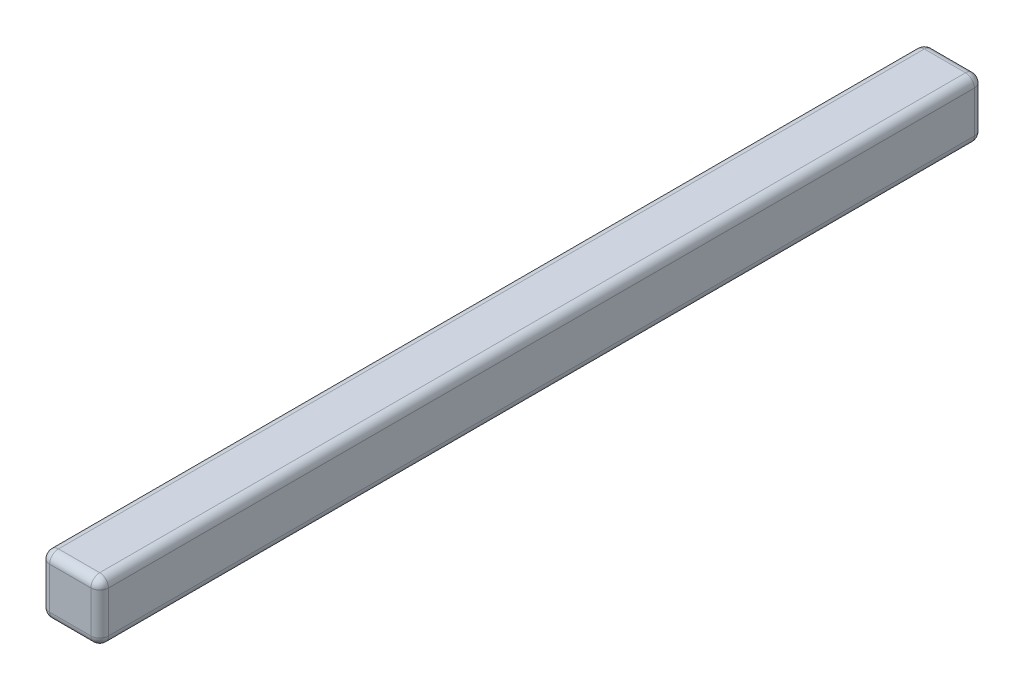
SolidWorks part; units mm, degrees
ref_plane "前视基准面" through (0, 0, 0) normal (0, 0, 1) x (1, 0, 0)
ref_plane "上视基准面" through (0, 0, 0) normal (0, 1, 0) x (1, 0, 0)
ref_plane "右视基准面" through (0, 0, 0) normal (1, 0, 0) x (0, 0, -1)
sketch "草图1" plane through (0, 0, 0) normal (0, 0, 1) x (1, 0, 0)
  line L1 (40, 31.125) -> (60, 31.125)
  line L2 (40, 31.125) -> (40, 11.0249)
  line L3 (40, 11.0249) -> (60, 11.0249)
  line L4 (60, 31.125) -> (60, 11.0249)
  dimension "D1" = 20
extrude "凸台-拉伸1" add sketch "草图1" along normal blind 300
fillet "圆角1" radius 3 12 edges at (40, 21.075, 300) (40, 21.075, 0) (40, 11.0249, 150) (50, 11.0249, 300) (50, 11.0249, 0) (60, 11.0249, 150) (60, 21.075, 300) (60, 21.075, 0) (60, 31.125, 150) (50, 31.125, 300) (40, 31.125, 150) (50, 31.125, 0)
